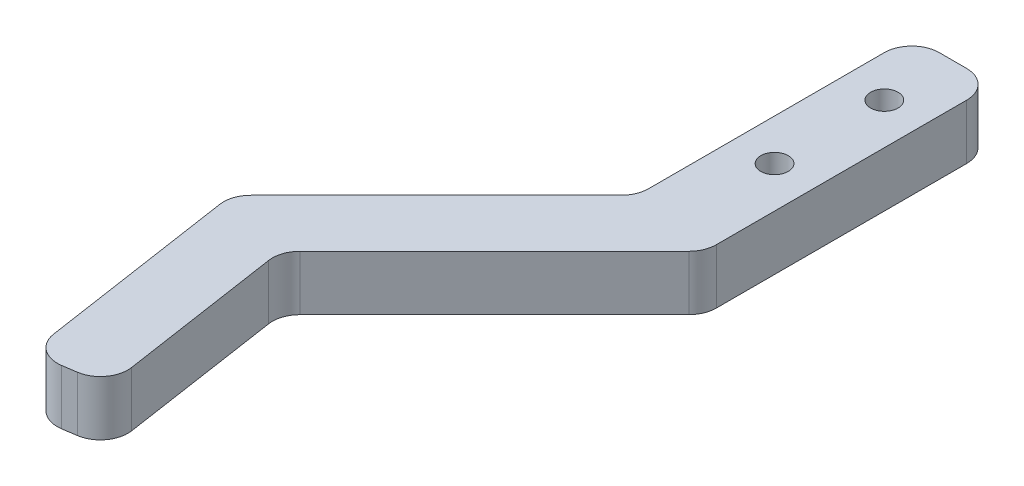
SolidWorks part; units mm, degrees
material "Thornel Mat VMA"
ref_plane "前视基准面" through (0, 0, 0) normal (0, 0, 1) x (1, 0, 0)
ref_plane "上视基准面" through (0, 0, 0) normal (0, 1, 0) x (1, 0, 0)
ref_plane "右视基准面" through (0, 0, 0) normal (1, 0, 0) x (0, 0, -1)
other "Configuration Table"
sketch "草图1" plane through (0, 0, 0) normal (0, 1, 0) x (1, 0, 0)
  line L0 (0, 0) -> (0, 50) construction
  line L1 (0, 0) -> (49.8304, 0) construction
  line L2 (0, 35) -> (25, 35) construction
  line L3 (25, 35) -> (25, 30) construction
  line L5 (25, 30) -> (15, 20) construction
  line L6 (25, -30) -> (15, -20) construction
  line L8 (25, -35) -> (25, -30) construction
  line L9 (0, -35) -> (25, -35) construction
  line L10 (0, 35) -> (0, -35) construction
  line L14 (25, 40) -> (30, 45)
  line L17 (30.2929, 38.2218) -> (36, 43.9289)
  line L18 (30, 45) -> (30, 65)
  line L19 (30, 65) -> (36, 65)
  line L20 (36, 65) -> (36, 43.9289)
  line L21 (33, 65) -> (33, 39.979) construction
  line L22 (0, 0) -> (25, 0) construction
  line L23 (25, 40) -> (15.2174, 30.2174)
  line L27 (0, -35) -> (71.4693, -35) construction
  line L28 (0, -35) -> (25, -35)
  line L29 (25, -35) -> (16, 25) construction
  line L30 (16, 25) -> (0, 25) construction
  line L31 (30.2929, 38.2218) -> (20.5362, 28.4651)
  line L32 (15.2174, 30.2174) -> (17.8, 13)
  line L33 (20.5362, 28.4651) -> (22.7447, 13.7417)
  line L34 (22.7447, 13.7417) -> (17.8, 13)
  arc A0 (15, -20) -> (15, 20) centre (0, 0) ccw construction
  circle A4 centre (33, 60) radius 1
  circle A5 centre (33, 52) radius 1
  point P16 (17.6649, 13.9005)
  point P26 (0, 0)
  dimension "D3" = 50
  dimension "D11" = 33
  dimension "D12" = 20
  dimension "D13" = 2
  dimension "D14" = 2
  dimension "D15" = 8
  dimension "D16" = 5
  dimension "D17" = 5
  dimension "D1" = 5
  dimension "D2" = 25
  dimension "D4" = 35
  dimension "D5" = 45
  dimension "D6" = 5
  dimension "D7" = 12
  dimension "D8" = 10
  dimension "D9" = 5
  dimension "D10" = 6
  dimension "D18" = 65
  dimension "D20" = 60
  dimension "D21" = 16
  dimension "D22" = 25
extrude "凸台-拉伸1" add sketch "草图1" along normal blind 4 contours L34 L33 L31 L17 L20 L19 L18 L14 L23 L32 A5 A4
fillet "圆角1" radius 2 8 edges at (30, 2, -45) (36, 2, -43.9289) (36, 2, -65) (30, 2, -65) (22.7447, 2, -13.7417) (17.8, 2, -13) (20.5362, 2, -28.4651) (15.2174, 2, -30.2174)
